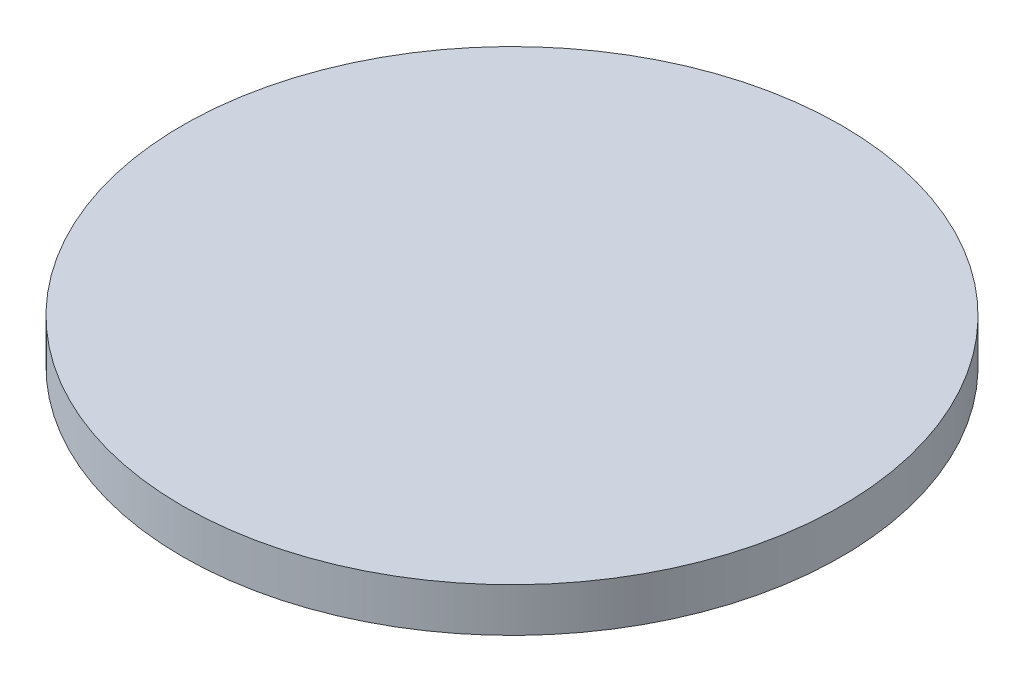
SolidWorks part; units mm, degrees
ref_plane "Front Plane" through (0, 0, 0) normal (0, 0, 1) x (1, 0, 0)
ref_plane "Top Plane" through (0, 0, 0) normal (0, 1, 0) x (1, 0, 0)
ref_plane "Right Plane" through (0, 0, 0) normal (1, 0, 0) x (0, 0, -1)
other "Configuration Table"
sketch "Sketch1" plane through (0, 0, 0) normal (0, 1, 0) x (1, 0, 0)
  circle A0 centre (0, 0) radius 30
extrude "KOLA330_boyun_daralma_D60" add sketch "Sketch1" along normal blind 4 from offset 108 separate body
